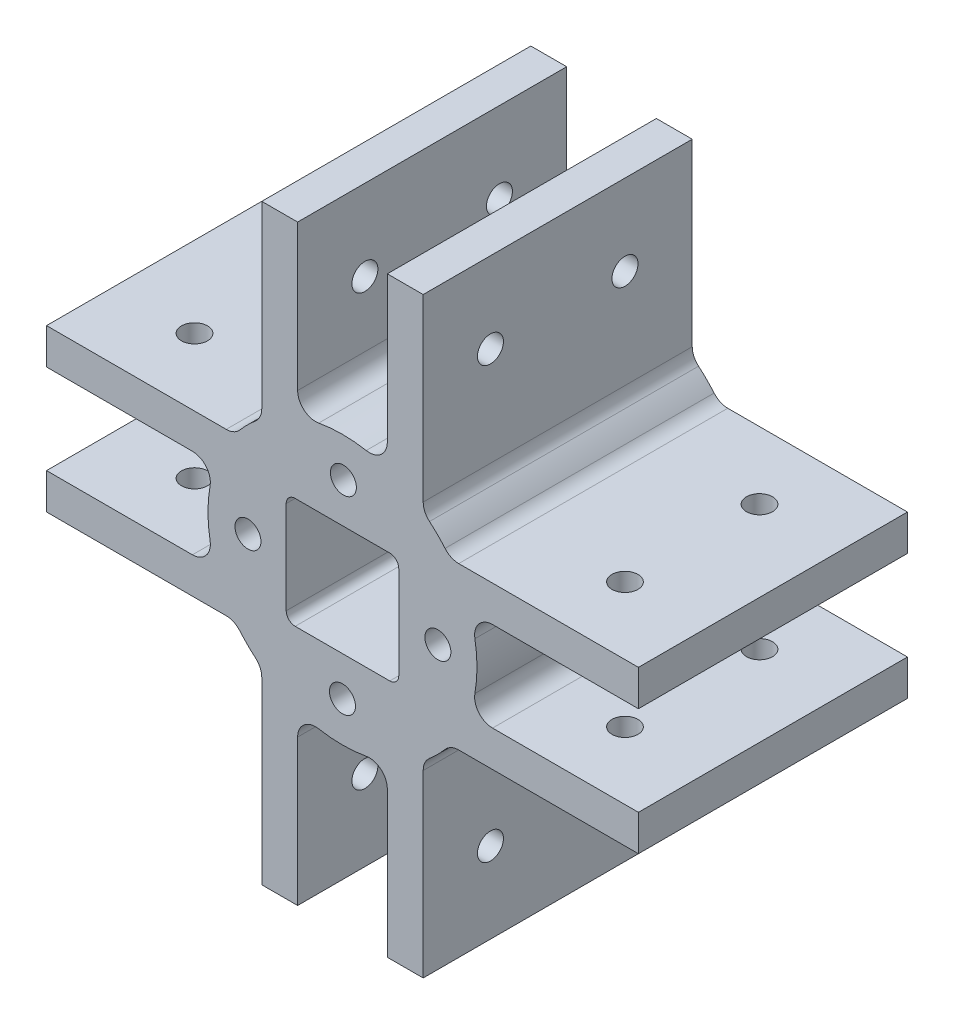
SolidWorks part; units mm, degrees
ref_plane "Front Plane" through (0, 0, 0) normal (0, 0, 1) x (1, 0, 0)
ref_plane "Top Plane" through (0, 0, 0) normal (0, 1, 0) x (1, 0, 0)
ref_plane "Right Plane" through (0, 0, 0) normal (1, 0, 0) x (0, 0, -1)
sketch "Sketch1" plane through (0, 0, 0) normal (0, 0, 1) x (1, 0, 0)
  circle A0 centre (0, 0) radius 15
  dimension "D2" = 30
extrude "Boss-Extrude1" add sketch "Sketch1" along normal mid plane 30
sketch "Sketch4" plane through (0, 0, 15) normal (0, 0, 1) x (1, 0, 0)
  line L0 (16.5, 0) -> (-16.5, 0) construction
  line L2 (-9, 0) -> (-5, 0)
  line L3 (0, 0) -> (0, 15.8331) construction
  line L4 (-9, 0) -> (-9, 33)
  line L5 (-9, 33) -> (-5, 33)
  line L6 (-5, 0) -> (-5, 33)
  line L7 (0, -16.5) -> (0, 16.5) construction
  line L8 (9, 33) -> (5, 33)
  line L9 (5, 0) -> (5, 33)
  line L10 (9, 0) -> (5, 0)
  line L11 (9, 0) -> (9, 33)
  dimension "D1" = 33
  dimension "D3" = 5
  dimension "D2" = 4
extrude "Boss-Extrude3" add sketch "Sketch4" against normal up to surface (30 mm away) up to face at (15, 0, -15)
fillet "Fillet2" radius 2 4 edges at (9, 12, 0) (5, 14.1421, 0) (-5, 14.1421, 0) (-9, 12, 0)
pattern_circular "CirPattern7" count 4 over 360 about axis through (0, 0, 0) along (0, 0, 1) of "Boss-Extrude3", "Fillet2"
sketch "Sketch7" plane through (-9, 0, 0) normal (-1, 0, 0) x (0, 0, 1)
  line L0 (-15, 33) -> (15, 33) construction
  line L1 (-15, 12.9615) -> (-15, 33) construction
  circle A0 centre (-7.5, 24) radius 1.45
  circle A1 centre (7.5, 24) radius 1.45
  circle A2 centre (22.5, 24) radius 1.45
  circle A3 centre (37.5, 24) radius 1.45
  circle A4 centre (52.5, 24) radius 1.45
  dimension "D1" = 2.9
  dimension "D2" = 9
  dimension "D3" = 7.5
  dimension "D4" = 5
extrude "Cut-Extrude2" cut sketch "Sketch7" against normal blind 27
pattern_circular "CirPattern9" count 4 over 360 of "Cut-Extrude2"
sketch "Sketch8" plane through (0, 0, 15) normal (0, 0, 1) x (1, 0, 0)
  line L2 (-6.275, 6.175) -> (6.275, 6.175)
  line L3 (-6.275, 6.175) -> (-6.275, -6.175)
  line L4 (-6.275, -6.175) -> (6.275, -6.175)
  line L5 (6.275, 6.175) -> (6.275, -6.175)
  line L6 (-6.275, 6.175) -> (6.275, -6.175) construction
  line L7 (-6.275, -6.175) -> (6.275, 6.175) construction
  point P5 (0, 0)
  point P14 (0, 0)
  dimension "D1" = 12.55
  dimension "D2" = 12.35
extrude "Cut-Extrude3" cut sketch "Sketch8" against normal up to next
sketch "Sketch9" plane through (0, 0, 15) normal (0, 0, 1) x (1, 0, 0)
  line L0 (16.5, 0) -> (-16.5, 0) construction
  line L1 (6.275, -6.175) -> (6.275, 6.175) construction
  circle A0 centre (10.6375, 0) radius 1.45
  circle A1 centre (0, -10.5375) radius 1.45
  circle A2 centre (-10.5375, 0.1) radius 1.45
  circle A3 centre (0.1, 10.6375) radius 1.45
  point P14 (0.05, 0.05)
  dimension "D1" = 2.9
  dimension "D2" = 4.3625
  dimension "D3" = 4
extrude "Cut-Extrude4" cut sketch "Sketch9" against normal blind 10
fillet "Fillet1" radius 1 4 edges at (-6.275, 6.175, 0) (6.275, 6.175, 0) (6.275, -6.175, 0) (-6.275, -6.175, 0)
mirror "Mirror1" about plane through (0, 0, 0) normal (0, 0, 1) of "Cut-Extrude4"
equation "\"drumDiameter\"= 30"
equation "\"D2@Sketch1\"=\"drumDiameter\""
equation "\"drumLength\"= 30"
equation "\"D1@Sketch4\"=\"drumDiameter\"*(0.5+\"drumAbove\")"
equation "\"foamThickness\"= 10"
equation "\"D3@Sketch4\"=\"foamThickness\"/2"
equation "\"drumAbove\"= 0.6"
equation "\"D2@Sketch7\"=\"drumDiameter\"*\"drumAbove\"/2"
equation "\"holderThicc\"= 4"
equation "\"D2@Sketch4\"=\"holderThicc\""
equation "\"D1@Boss-Extrude1\"=\"drumLength\""
equation "\"squareBarLength\"= 12.55"
equation "\"D1@Sketch8\"=\"squareBarLength\""
equation "\"D2@Sketch9\"=(\"drumDiameter\"/2-\"squareBarLength\"/2)/2"
equation "\"squareBarShortLen\"= 12.35"
equation "\"D2@Sketch8\"=\"squareBarShortLen\""
